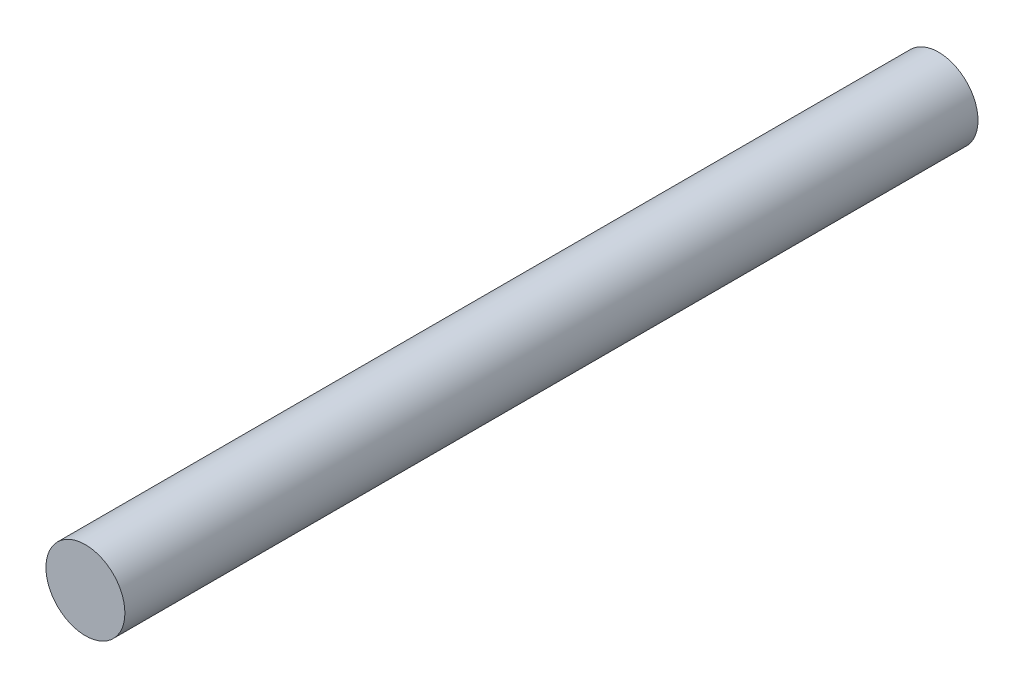
SolidWorks part; units mm, degrees
ref_plane "정면" through (0, 0, 0) normal (0, 0, 1) x (1, 0, 0)
ref_plane "윗면" through (0, 0, 0) normal (0, 1, 0) x (1, 0, 0)
ref_plane "우측면" through (0, 0, 0) normal (1, 0, 0) x (0, 0, -1)
sketch "스케치1" plane through (0, 0, 0) normal (0, 0, 1) x (1, 0, 0)
  circle A0 centre (0, 0) radius 0.995
  dimension "D1" = 1.99
extrude "보스-돌출1" add sketch "스케치1" along normal blind 21.5
